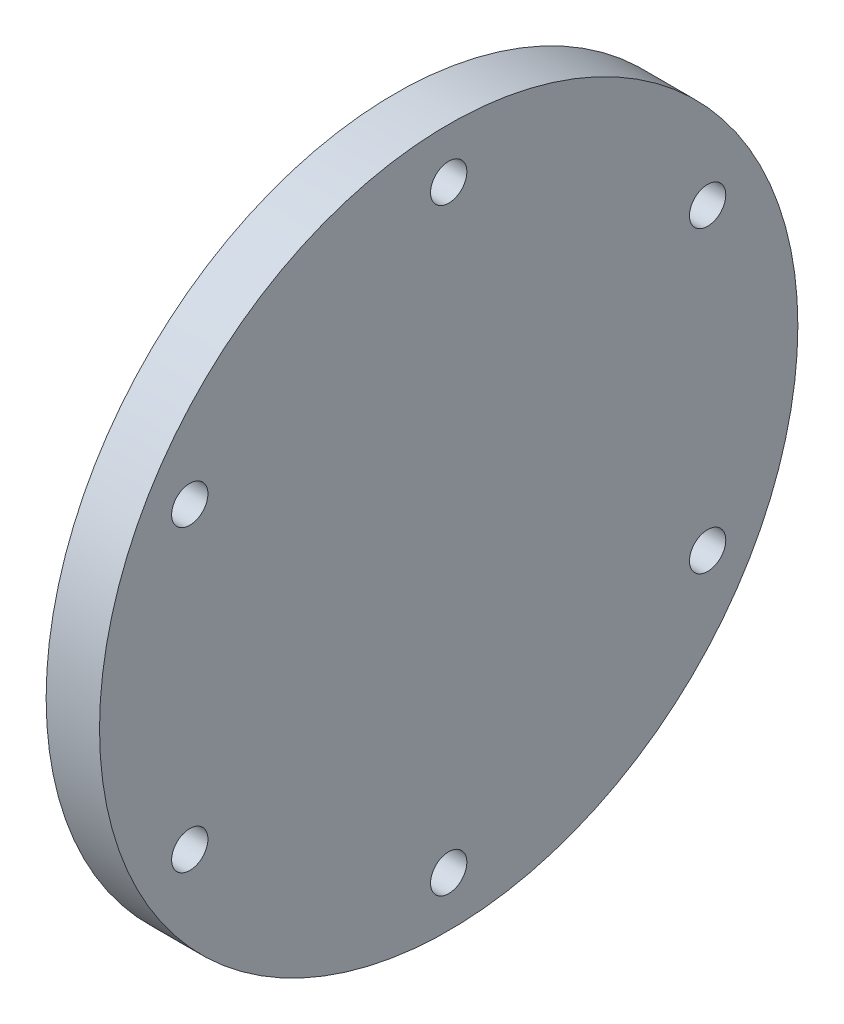
SolidWorks part; units mm, degrees
material "6063-T5"
ref_plane "Front" through (0, 0, 0) normal (0, 0, 1) x (1, 0, 0)
ref_plane "Top" through (0, 0, 0) normal (0, 1, 0) x (1, 0, 0)
ref_plane "Right" through (0, 0, 0) normal (1, 0, 0) x (0, 0, -1)
sketch "Croquis1" plane through (0, 0, 0) normal (1, 0, 0) x (0, 0, -1)
  circle A0 centre (0, 0) radius 32.7
  dimension "D1" = 65.4
extrude "Saliente-Extruir1" add sketch "Croquis1" along normal blind 5
hole_wizard "Taladro de margen para M31" positions "Croquis2" profile "Croquis3" hole size "M3" standard "Ansi Metric"
sketch "Croquis2" plane through (5, 0, 0) normal (1, 0, 0) x (0, 0, -1)
  line L0 (0, 2.75) -> (0, -2.75) construction
  line L1 (2.75, 0) -> (-2.75, 0) construction
  point P0 (0, 28)
  point P12 (24.2487, 14)
  point P13 (24.2487, -14)
  point P14 (0, -28)
  point P15 (-24.2487, -14)
  point P16 (-24.2487, 14)
  dimension "D1" = 28
  dimension "D3" = 28
  dimension "D2" = 6
sketch "Croquis3" plane through (5, 28, 0) normal (0, 1, 0) x (0, 0, -1)
  line L0 (0, 0) -> (0, 11.0215)
  line L1 (0, 11.0215) -> (1.7, 10)
  line L2 (1.7, 10) -> (1.7, 0)
  line L5 (1.7, 0) -> (0, 0)
  line L10 (0, 11.0215) -> (-1.7, 10) construction
  line L11 (0, -6.35) -> (0, 107.95) construction
  dimension "Diámetro de taladro" = 3.4
  dimension "Profundidad de taladro" = 10
  dimension "Ángulo de perforador" = 118
